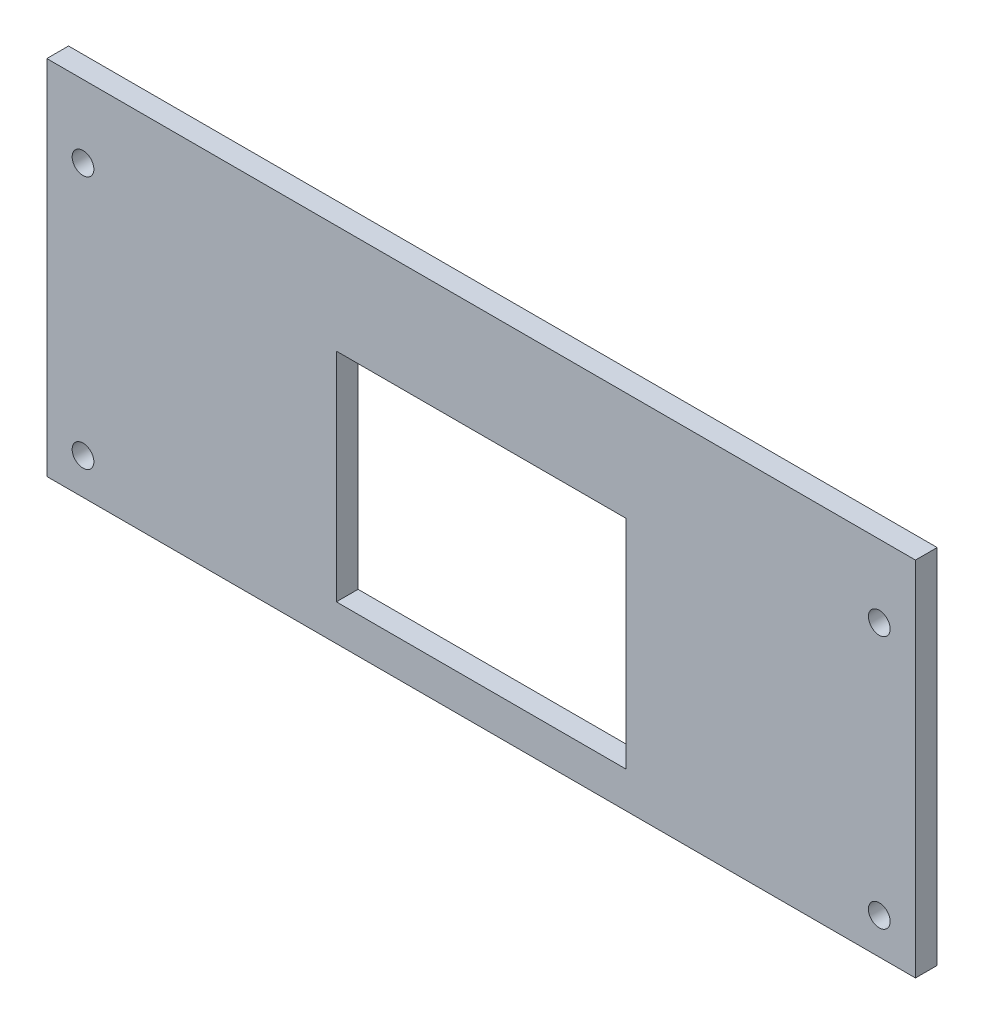
SolidWorks part; units mm, degrees
ref_plane "Plan de face" through (0, 0, 0) normal (0, 0, 1) x (1, 0, 0)
ref_plane "Plan de dessus" through (0, 0, 0) normal (0, 1, 0) x (1, 0, 0)
ref_plane "Plan de droite" through (0, 0, 0) normal (1, 0, 0) x (0, 0, -1)
sketch "Esquisse1" plane through (0, 0, 0) normal (0, 0, 1) x (1, 0, 0)
  line L0 (-55, 25) -> (-55, -25) construction
  line L1 (60, -25) -> (-60, -25)
  line L2 (60, -25) -> (60, 25)
  line L3 (60, 25) -> (-60, 25)
  line L4 (-60, -25) -> (-60, 25)
  line L5 (60, -25) -> (-60, 25) construction
  line L6 (60, 25) -> (-60, -25) construction
  line L7 (0, 25) -> (0, -25) construction
  line L9 (20, -20) -> (-20, -20)
  line L10 (20, -20) -> (20, 10)
  line L11 (20, 10) -> (-20, 10)
  line L12 (-20, -20) -> (-20, 10)
  line L13 (20, -20) -> (-20, 10) construction
  line L14 (20, 10) -> (-20, -20) construction
  circle A0 centre (-55, 15) radius 1.5
  circle A1 centre (-55, -20) radius 1.5
  circle A2 centre (55, -20) radius 1.5
  circle A3 centre (55, 15) radius 1.5
  point P0 (0, 0)
  point P20 (0, -5)
  dimension "D4" = 3
  dimension "D1" = 120
  dimension "D2" = 50
  dimension "D3" = 5
  dimension "D5" = 10
  dimension "D6" = 5
  dimension "D7" = 30
  dimension "D8" = 30
  dimension "D9" = 40
extrude "Boss.-Extru.1" add sketch "Esquisse1" along normal blind 3
